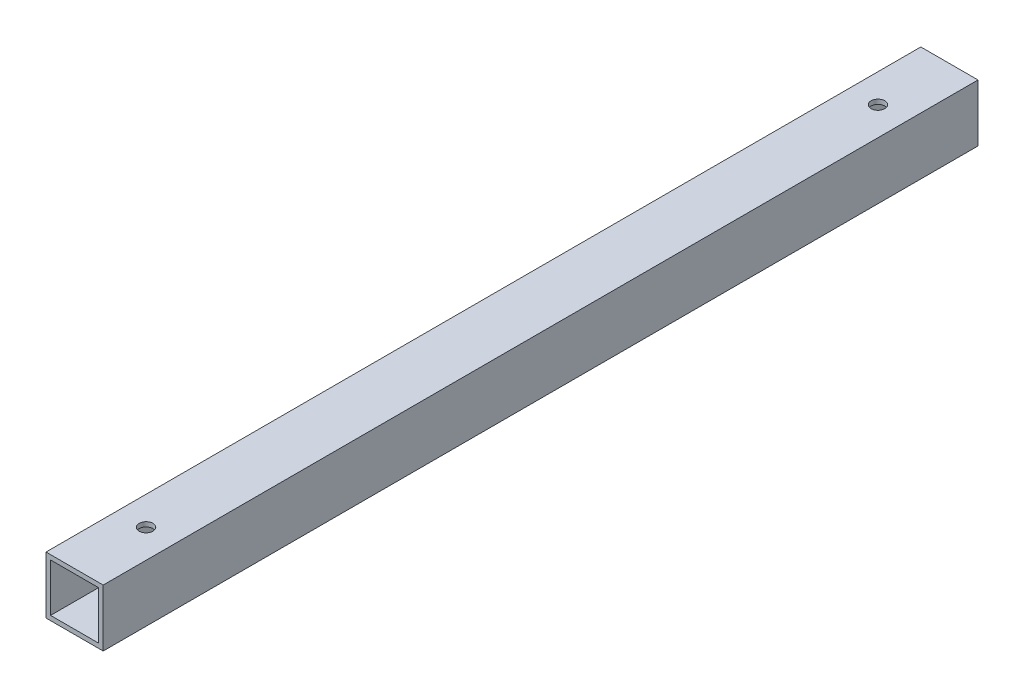
SolidWorks part; units mm, degrees
material "AISI 1010 钢，热轧条材"
ref_plane "前视基准面" through (0, 0, 0) normal (0, 0, 1) x (1, 0, 0)
ref_plane "上视基准面" through (0, 0, 0) normal (0, 1, 0) x (1, 0, 0)
ref_plane "右视基准面" through (0, 0, 0) normal (1, 0, 0) x (0, 0, -1)
sketch "草图1" plane through (0, 0, 0) normal (0, 0, 1) x (1, 0, 0)
  line L0 (-21, -21) -> (-21, 21)
  line L1 (-25, -25) -> (25, -25)
  line L2 (-25, -25) -> (-25, 25)
  line L3 (-25, 25) -> (25, 25)
  line L4 (25, -25) -> (25, 25)
  line L5 (-25, -25) -> (25, 25) construction
  line L6 (-25, 25) -> (25, -25) construction
  line L7 (-21, 21) -> (21, 21)
  line L8 (21, -21) -> (21, 21)
  line L9 (-21, -21) -> (21, -21)
  point P0 (0, 0)
  dimension "D1" = 50
  dimension "D2" = 50
  dimension "D3" = 4
extrude "凸台-拉伸1" add sketch "草图1" along normal mid plane 765 contours L1 L4 L3 L2 L9 L0 L7 L8
sketch "草图2" plane through (0, 25, 0) normal (0, 1, 0) x (1, 0, 0)
  line L0 (0, 320) -> (0, -320) construction
  circle A0 centre (0, 320) radius 6
  circle A1 centre (0, -320) radius 6
  point P4 (0, 0)
  dimension "D2" = 12
  dimension "D1" = 640
extrude "切除-拉伸1" cut sketch "草图2" against normal through all contours A0 | A1
